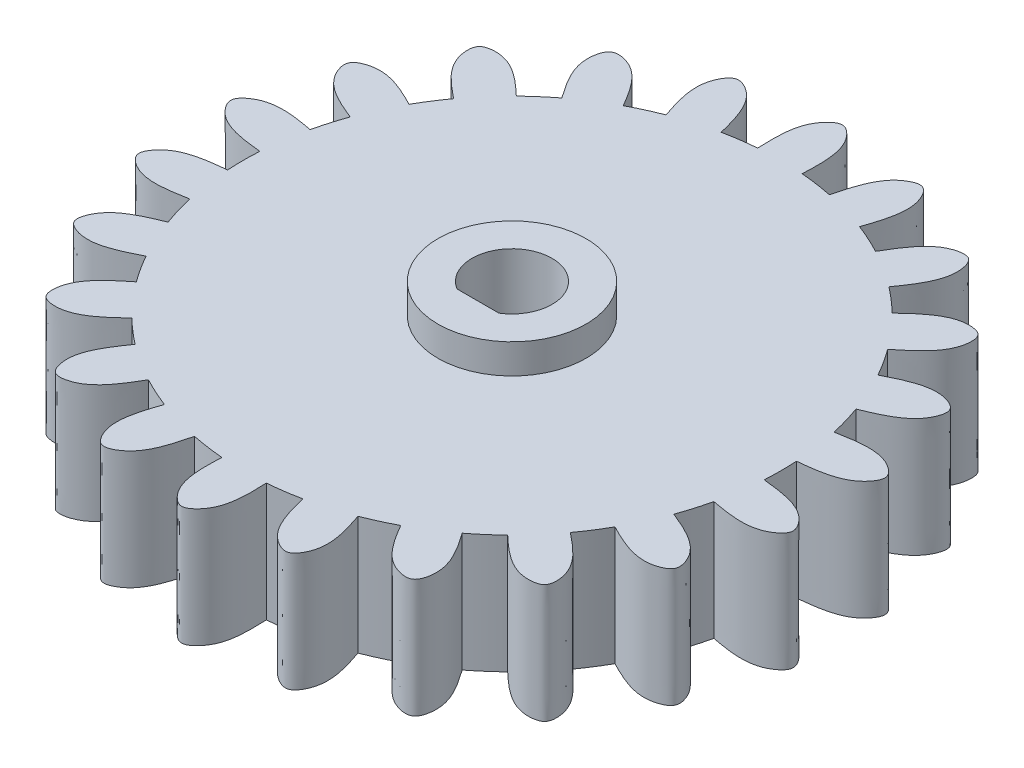
SolidWorks part; units mm, degrees
ref_plane "Front Plane" through (0, 0, 0) normal (0, 0, 1) x (1, 0, 0)
ref_plane "Top Plane" through (0, 0, 0) normal (0, 1, 0) x (1, 0, 0)
ref_plane "Right Plane" through (0, 0, 0) normal (1, 0, 0) x (0, 0, -1)
sketch "Sketch1" plane through (0, 0, 0) normal (0, 1, 0) x (1, 0, 0)
  line L0 (0, 0) -> (0, 10) construction
  circle A12 centre (0, 0) radius 18.145
  point P43 (0, 0)
  dimension "D1" = 36.29
extrude "Boss-Extrude1" add sketch "Sketch1" along normal blind 10
sketch "Sketch4" plane through (0, 0, 0) normal (0, -1, 0) x (1, 0, 0)
  line L0 (-1.5, -18.0829) -> (1.5, -18.0829)
  circle A1 centre (0, 0) radius 18.145 construction
  spline S0 degree 3 poles (1.5, -18.0829) (1.5223, -18.6481) (1.5744, -19.9649) (1.1993, -21.5784) (0, -22.4862) (-1.1993, -21.5784) (-1.5744, -19.9649) (-1.5223, -18.6481) (-1.5, -18.0829) knots 0 0 0 0 0.178316 0.415433 0.5 0.584567 0.821684 1 1 1 1
  dimension "D1" = 3
  dimension "D2" = 3
  dimension "D3" = 4.2143
  dimension "D4" = 1.4
  dimension "D5" = 0.4
  dimension "D6" = 0.7
  dimension "D7" = 1.7
sketch "Sketch2" plane through (0, 10, 0) normal (0, 1, 0) x (1, 0, 0)
  circle A0 centre (0, 0) radius 5
  dimension "D1" = 10
extrude "Boss-Extrude2" add sketch "Sketch2" along normal blind 2
extrude "Boss-Extrude5" add sketch "Sketch4" against normal blind 10
pattern_circular "CirPattern1" count 22 over 360 of "Boss-Extrude5"
sketch "Sketch5" plane through (0, 12, 0) normal (0, 1, 0) x (1, 0, 0)
  line L0 (1.4142, -2.3) -> (-1.4142, -2.3)
  arc A0 (1.4142, -2.3) -> (-1.4142, -2.3) centre (0, 0) ccw
  point P5 (0, -2.3)
  dimension "D1" = 5.4
  dimension "D2" = 2.3
extrude "Cut-Extrude1" cut sketch "Sketch5" against normal through all contours A0 L0
sketch "Sketch6" plane through (0, 0, 0) normal (0, -1, 0) x (1, 0, 0)
  circle A2 centre (0, 0) radius 36.4787
extrude "Cut-Extrude2" cut sketch "Sketch6" against normal blind 2 contours A2
